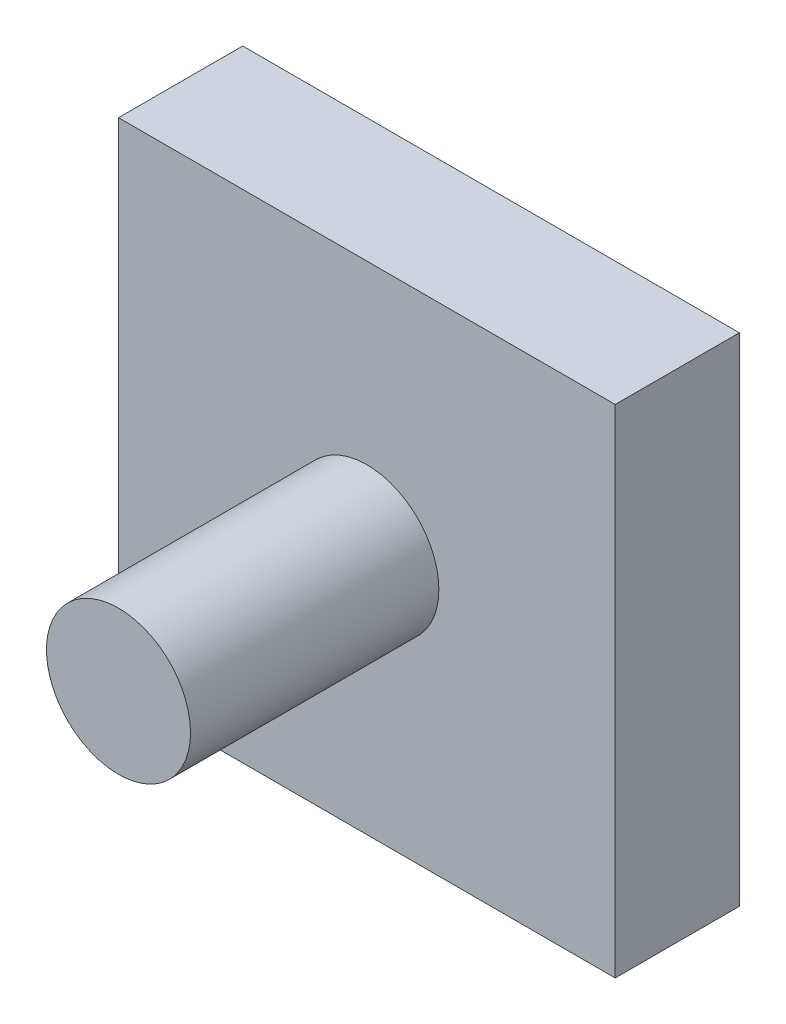
SolidWorks part; units mm, degrees
ref_plane "Plan de face" through (0, 0, 0) normal (0, 0, 1) x (1, 0, 0)
ref_plane "Plan de dessus" through (0, 0, 0) normal (0, 1, 0) x (1, 0, 0)
ref_plane "Plan de droite" through (0, 0, 0) normal (1, 0, 0) x (0, 0, -1)
sketch "Esquisse1" plane through (0, 0, 0) normal (0, 0, 1) x (1, 0, 0)
  line L1 (-100, -100) -> (100, -100)
  line L2 (-100, -100) -> (-100, 100)
  line L3 (-100, 100) -> (100, 100)
  line L4 (100, -100) -> (100, 100)
  line L5 (-100, -100) -> (100, 100) construction
  line L6 (-100, 100) -> (100, -100) construction
  point P0 (0, 0)
  dimension "D1" = 200
  dimension "D2" = 200
extrude "Boss.-Extru.1" add sketch "Esquisse1" along normal blind 50
sketch "Esquisse2" plane through (0, 0, 50) normal (0, 0, 1) x (1, 0, 0)
  circle A0 centre (0, 0) radius 29
extrude "Boss.-Extru.2" add sketch "Esquisse2" along normal blind 100
